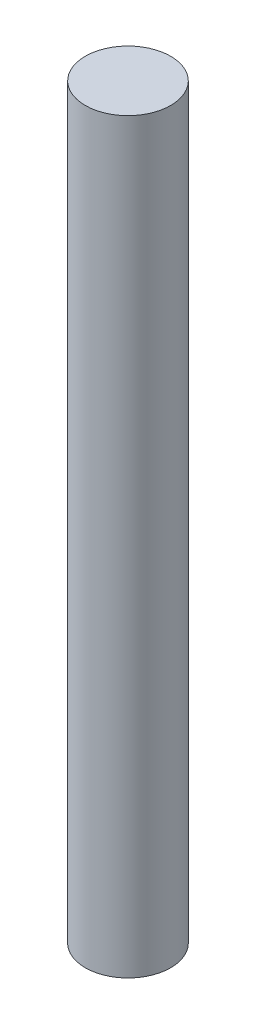
SolidWorks part; units mm, degrees
ref_plane "前视基准面" through (0, 0, 0) normal (0, 0, 1) x (1, 0, 0)
ref_plane "上视基准面" through (0, 0, 0) normal (0, 1, 0) x (1, 0, 0)
ref_plane "右视基准面" through (0, 0, 0) normal (1, 0, 0) x (0, 0, -1)
other "Configuration Table"
sketch "草图1" plane through (0, 0, 0) normal (0, 1, 0) x (1, 0, 0)
  circle A0 centre (0, 0) radius 2
  dimension "D1" = 4
extrude "凸台-拉伸1" add sketch "草图1" along normal blind 35
